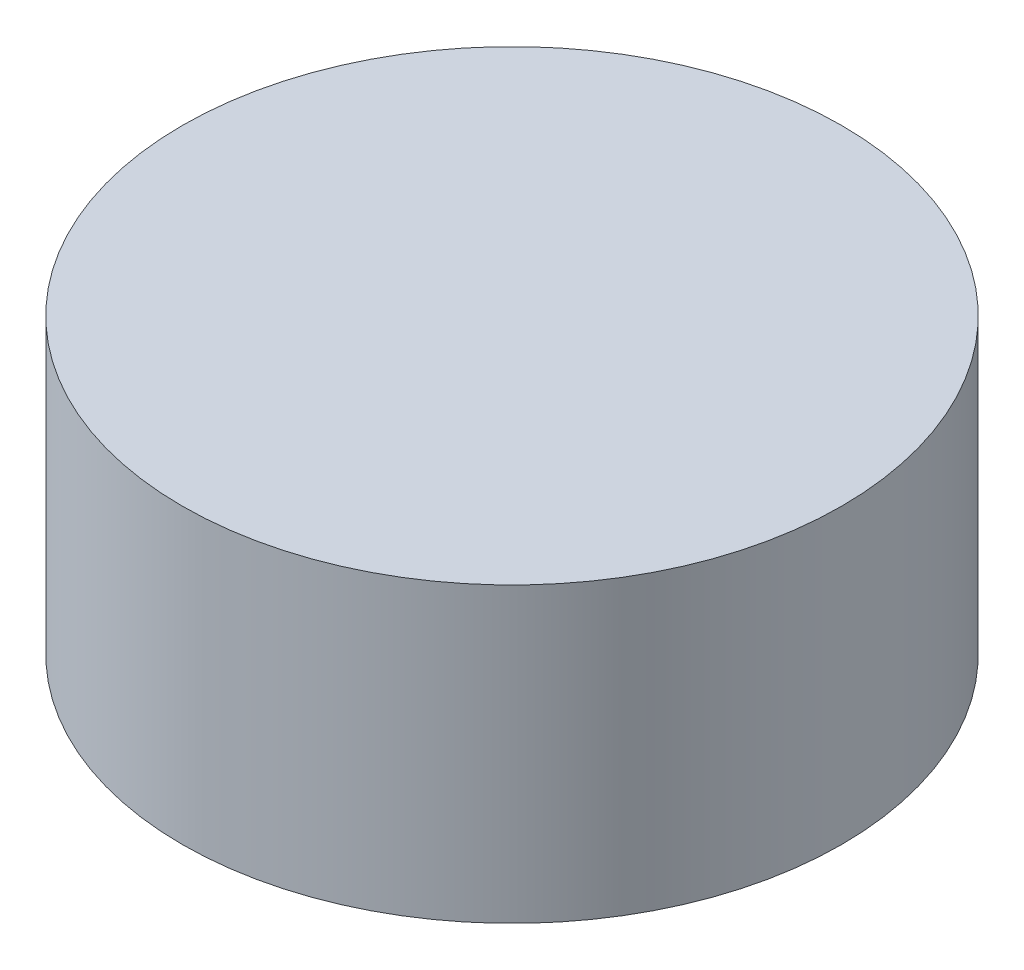
SolidWorks part; units mm, degrees
ref_plane "Alzado" through (0, 0, 0) normal (0, 0, 1) x (1, 0, 0)
ref_plane "Planta" through (0, 0, 0) normal (0, 1, 0) x (1, 0, 0)
ref_plane "Vista lateral" through (0, 0, 0) normal (1, 0, 0) x (0, 0, -1)
sketch "Croquis1" plane through (0, 0, 0) normal (0, 1, 0) x (1, 0, 0)
  circle A0 centre (0, 0) radius 13.5
  dimension "D1" = 27
extrude "Saliente-Extruir1" add sketch "Croquis1" along normal blind 12
